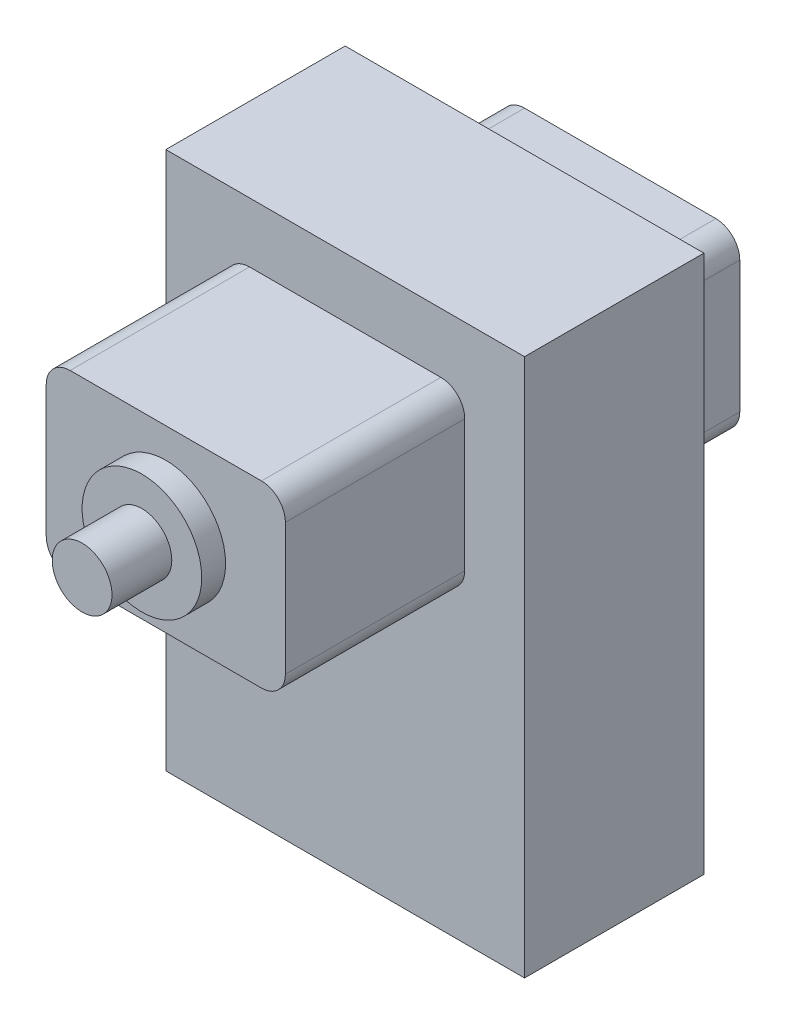
SolidWorks part; units mm, degrees
ref_plane "Ön Düzlem" through (0, 0, 0) normal (0, 0, 1) x (1, 0, 0)
ref_plane "Üst Düzlem" through (0, 0, 0) normal (0, 1, 0) x (1, 0, 0)
ref_plane "Sağ Düzlem" through (0, 0, 0) normal (1, 0, 0) x (0, 0, -1)
sketch "Sketch3" plane through (0, 0, 0) normal (0, 0, 1) x (1, 0, 0)
  line L1 (-30, 45) -> (0, 45)
  line L2 (-30, 45) -> (-30, 0)
  line L3 (-30, 0) -> (0, 0)
  line L4 (0, 45) -> (0, 0)
  dimension "D1" = 30
  dimension "D2" = 45
extrude "Boss-Extrude1" add sketch "Sketch3" along normal blind 15
sketch "Sketch4" plane through (0, 0, 15) normal (0, 0, 1) x (1, 0, 0)
  line L0 (0, 0) -> (0, 45) construction
  line L1 (-25, 40) -> (-5, 40)
  line L2 (-25, 40) -> (-25, 25)
  line L3 (-25, 25) -> (-5, 25)
  line L4 (-5, 40) -> (-5, 25)
  line L5 (0, 45) -> (-30, 45) construction
  line L6 (-30, 45) -> (-30, 0) construction
  dimension "D1" = 15
  dimension "D2" = 5
  dimension "D3" = 5
  dimension "D4" = 5
extrude "Boss-Extrude2" add sketch "Sketch4" along normal blind 15
sketch "Sketch5" plane through (0, 0, 0) normal (0, 0, -1) x (-1, 0, 0)
  line L0 (30, 45) -> (30, 0) construction
  line L1 (5, 40) -> (25, 40)
  line L2 (5, 40) -> (5, 25)
  line L3 (5, 25) -> (25, 25)
  line L4 (25, 40) -> (25, 25)
  line L5 (0, 0) -> (0, 45) construction
  line L6 (0, 45) -> (30, 45) construction
  dimension "D1" = 15
  dimension "D2" = 5
  dimension "D3" = 5
  dimension "D4" = 5
extrude "Boss-Extrude3" add sketch "Sketch5" along normal blind 8
fillet "Fillet1" radius 2 8 edges at (-25, 40, 22.5) (-25, 25, 22.5) (-5, 25, 22.5) (-5, 40, 22.5) (-5, 25, -4) (-25, 25, -4) (-5, 40, -4) (-25, 40, -4)
sketch "Sketch6" plane through (0, 0, 30) normal (0, 0, 1) x (1, 0, 0)
  line L0 (-5, 27) -> (-5, 38) construction
  line L1 (-23, 25) -> (-7, 25) construction
  circle A0 centre (-15, 32.5) radius 5
  point P4 (-5, 32.5)
  dimension "D1" = 10
  dimension "D2" = 10
  dimension "D3" = 7.5
extrude "Boss-Extrude4" add sketch "Sketch6" along normal blind 2
sketch "Sketch7" plane through (0, 0, 32) normal (0, 0, 1) x (1, 0, 0)
  circle A0 centre (-15, 32.5) radius 2.5
  circle A1 centre (-15, 32.5) radius 5 construction
  dimension "D1" = 5
extrude "Boss-Extrude5" add sketch "Sketch7" along normal blind 5 contours A0
